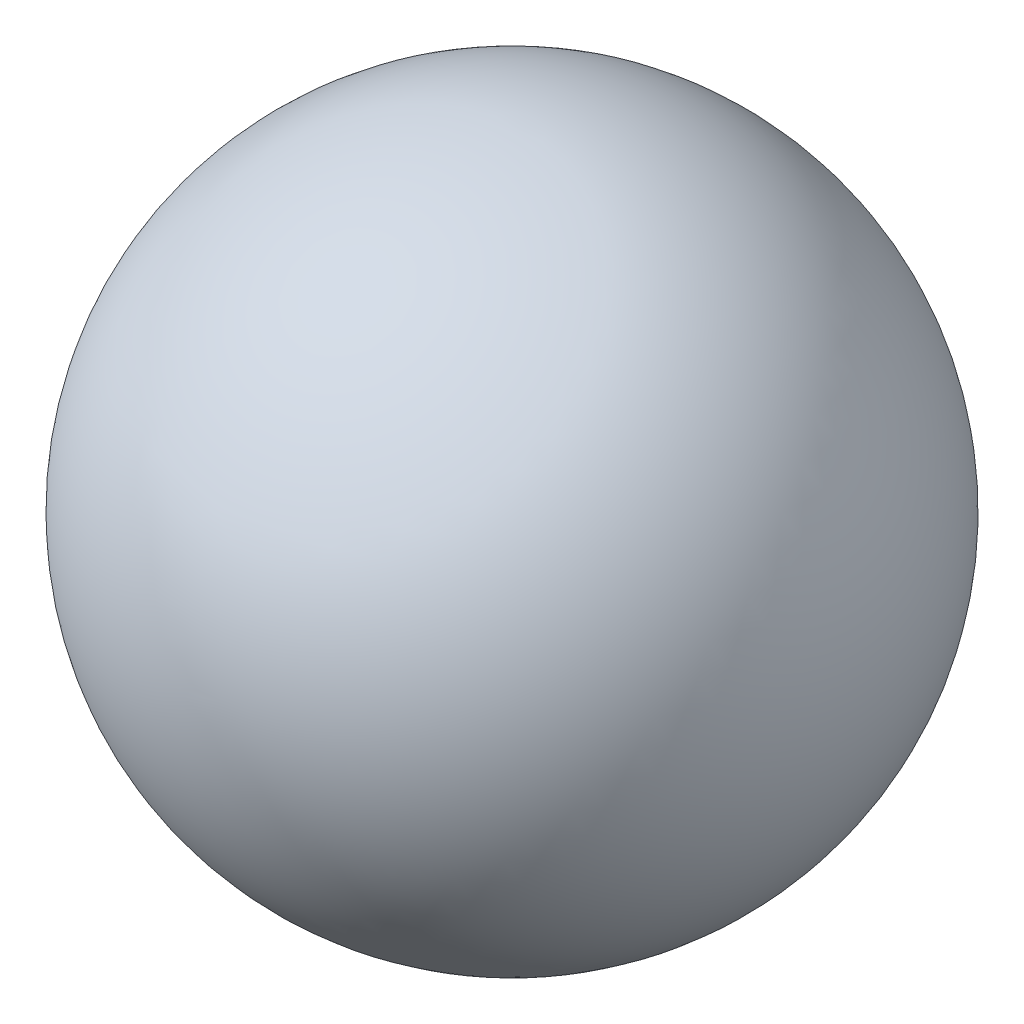
SolidWorks part; units mm, degrees
ref_plane "前视基准面" through (0, 0, 0) normal (0, 0, 1) x (1, 0, 0)
ref_plane "上视基准面" through (0, 0, 0) normal (0, 1, 0) x (1, 0, 0)
ref_plane "右视基准面" through (0, 0, 0) normal (1, 0, 0) x (0, 0, -1)
sketch "草图1" plane through (0, 0, 0) normal (0, 1, 0) x (1, 0, 0)
  line L0 (0, 37.1985) -> (0, -31.6678) construction
  line L1 (0, 10) -> (0, -10)
  arc A0 (0, -10) -> (0, 10) centre (0, 0) ccw
  dimension "D1" = 10
revolve "旋转1" add sketch "草图1" angle 360 about L0
sketch "草图2" plane through (0, 0, 0) normal (0, 1, 0) x (1, 0, 0)
  circle A0 centre (0, 0) radius 2.5
  dimension "D1" = 5
extrude "切除-拉伸1" cut sketch "草图2" against normal through all contours A0
